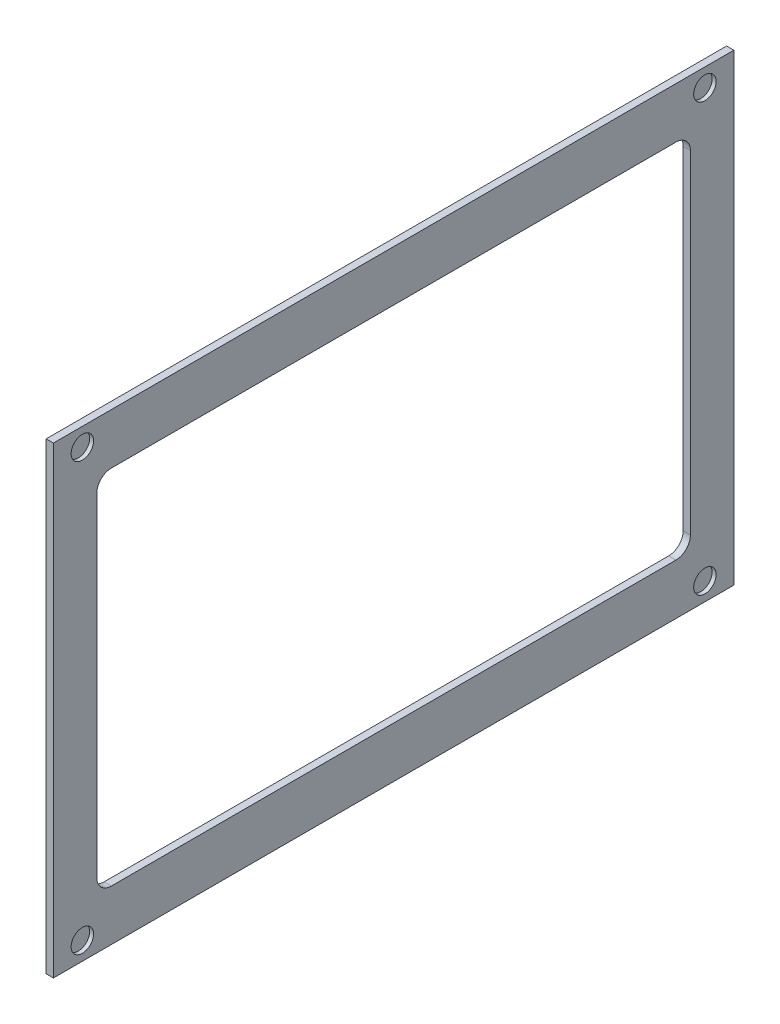
SolidWorks part; units mm, degrees
ref_plane "前视基准面" through (0, 0, 0) normal (0, 0, 1) x (1, 0, 0)
ref_plane "上视基准面" through (0, 0, 0) normal (0, 1, 0) x (1, 0, 0)
ref_plane "右视基准面" through (0, 0, 0) normal (1, 0, 0) x (0, 0, -1)
sketch "草图1" plane through (0, 0, 0) normal (1, 0, 0) x (0, 0, -1)
  line L0 (-133.672, 102.2392) -> (54.328, 102.2392)
  line L1 (-133.672, 102.2392) -> (-133.672, -25.7608)
  line L2 (-133.672, -25.7608) -> (54.328, -25.7608)
  line L3 (54.328, 102.2392) -> (54.328, -25.7608)
extrude "凸台-拉伸1" add sketch "草图1" along normal blind 2
sketch "草图2" plane through (0, 0, 0) normal (-1, 0, 0) x (0, 0, 1)
  line L0 (133.672, -25.7608) -> (-54.328, -25.7608) construction
  line L1 (121.672, -13.7608) -> (-42.328, -13.7608)
  line L2 (121.672, -13.7608) -> (121.672, 90.2392)
  line L3 (121.672, 90.2392) -> (-42.328, 90.2392)
  line L4 (-42.328, -13.7608) -> (-42.328, 90.2392)
  line L5 (-54.328, 102.2392) -> (133.672, 102.2392) construction
  line L6 (133.672, 102.2392) -> (133.672, -25.7608) construction
  line L7 (-54.328, -25.7608) -> (-54.328, 102.2392) construction
  dimension "D1" = 12
  dimension "D2" = 12
  dimension "D3" = 12
  dimension "D4" = 12
extrude "切除-拉伸1" [suppressed] cut sketch "草图2" against normal blind 10
fillet "圆角1" [suppressed] radius 2
sketch "草图3" [suppressed] plane through (0, 0, 0) normal (-1, 0, 0) x (0, 0, 1)
  line L0 (133.672, 102.2392) -> (133.672, -25.7608) construction
  line L1 (121.672, -3.7608) -> (-42.328, -3.7608)
  line L2 (121.672, -3.7608) -> (121.672, 80.2392)
  line L3 (121.672, 80.2392) -> (-42.328, 80.2392)
  line L4 (-42.328, -3.7608) -> (-42.328, 80.2392)
  line L5 (-54.328, -25.7608) -> (-54.328, 102.2392) construction
  line L6 (-54.328, 102.2392) -> (133.672, 102.2392) construction
  line L7 (133.672, -25.7608) -> (-54.328, -25.7608) construction
  dimension "D1" = 12
  dimension "D2" = 12
  dimension "D3" = 22
  dimension "D4" = 22
other "填充阵列1" [suppressed] parameters "D10"=2.5, "D5"=0, "D6"=0, "D4"=4, "D9"=861, "D3"=0
sketch "草图8" plane through (2, 0, 0) normal (1, 0, 0) x (0, 0, -1)
  line L0 (-133.672, 102.2392) -> (-133.672, -25.7608) construction
  line L1 (54.328, 102.2392) -> (-133.672, 102.2392) construction
  line L3 (-133.672, -25.7608) -> (54.328, -25.7608) construction
  line L5 (-125.672, 97.2392) -> (46.328, 97.2392) construction
  line L6 (-125.672, 97.2392) -> (-125.672, -20.7608) construction
  line L7 (-125.672, -20.7608) -> (46.328, -20.7608) construction
  line L8 (46.328, 97.2392) -> (46.328, -20.7608) construction
  circle A0 centre (-125.672, 97.2392) radius 3.1
  circle A1 centre (46.328, 97.2392) radius 3.1
  circle A2 centre (-125.672, -20.7608) radius 3.1
  circle A3 centre (46.328, -20.7608) radius 3.1
  dimension "D1" = 8
  dimension "D5" = 5
  dimension "D2" = 5
extrude "切除-拉伸5" cut sketch "草图8" against normal blind 1.1
sketch "草图9" plane through (2, 0, 0) normal (1, 0, 0) x (0, 0, -1)
  line L0 (54.328, 102.2392) -> (-133.672, 102.2392) construction
  line L1 (-133.672, 102.2392) -> (54.328, 102.2392)
  line L2 (-133.672, 102.2392) -> (-133.672, 92.2392)
  line L3 (-133.672, 92.2392) -> (54.328, 92.2392)
  line L4 (54.328, 102.2392) -> (54.328, 92.2392)
  line L5 (-133.672, 102.2392) -> (-133.672, -25.7608) construction
  line L6 (54.328, -25.7608) -> (54.328, 102.2392) construction
  line L8 (-133.672, -25.7608) -> (54.328, -25.7608)
  line L9 (-133.672, -25.7608) -> (-133.672, -15.7608)
  line L10 (-133.672, -15.7608) -> (54.328, -15.7608)
  line L11 (54.328, -25.7608) -> (54.328, -15.7608)
  dimension "D1" = 10
  dimension "D2" = 10
extrude "切除-拉伸6" [suppressed] cut sketch "草图9" against normal blind 1
sketch "草图10" plane through (0, 0, 0) normal (-1, 0, 0) x (0, 0, 1)
  line L0 (133.672, 38.2392) -> (77.672, 38.2392) construction
  line L1 (133.672, 102.2392) -> (133.672, -25.7608) construction
  circle A0 centre (77.672, 38.2392) radius 45
extrude "切除-拉伸7" [suppressed] cut sketch "草图10" against normal blind 10
sketch "草图11" plane through (0, 0, 0) normal (-1, 0, 0) x (0, 0, 1)
  line L0 (133.672, 102.2392) -> (133.672, -25.7608) construction
  line L1 (121.672, -11.7608) -> (-42.328, -11.7608)
  line L2 (121.672, -11.7608) -> (121.672, 88.2392)
  line L3 (121.672, 88.2392) -> (-42.328, 88.2392)
  line L4 (-42.328, -11.7608) -> (-42.328, 88.2392)
  line L5 (-54.328, -25.7608) -> (-54.328, 102.2392) construction
  line L6 (133.672, -25.7608) -> (-54.328, -25.7608) construction
  line L7 (-54.328, 102.2392) -> (133.672, 102.2392) construction
  dimension "D1" = 12
  dimension "D2" = 12
  dimension "D3" = 14
  dimension "D4" = 14
extrude "切除-拉伸8" cut sketch "草图11" against normal blind 10
fillet "圆角2" radius 4 4 edges at (1, 88.2392, -42.328) (1, 88.2392, 121.672) (1, -11.7608, -42.328) (1, -11.7608, 121.672)
